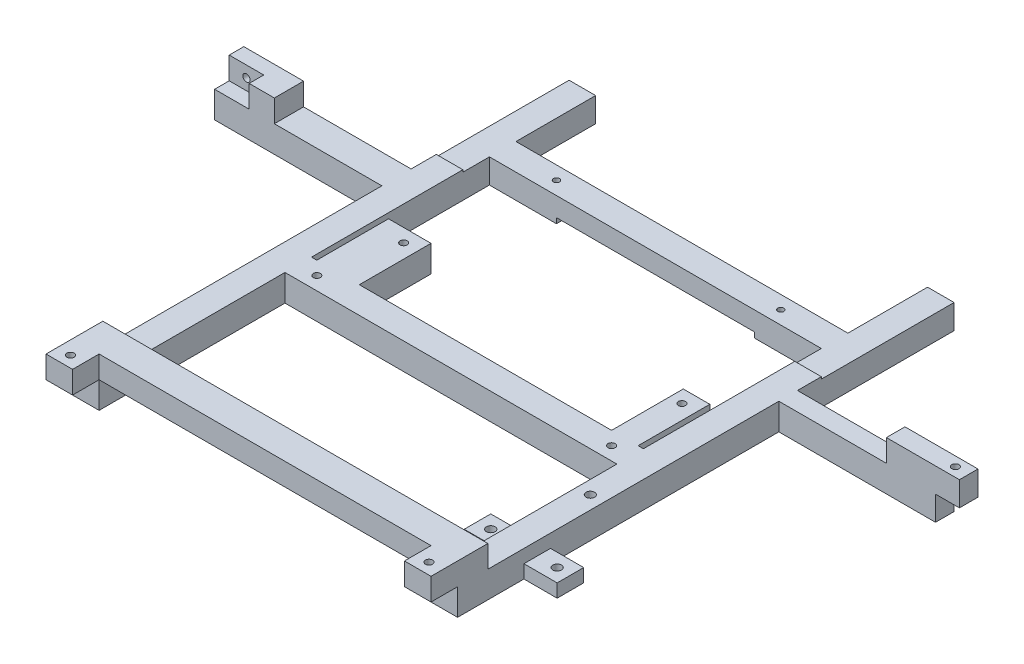
SolidWorks part; units mm, degrees
ref_plane "Front Plane" through (0, 0, 0) normal (0, 0, 1) x (1, 0, 0)
ref_plane "Top Plane" through (0, 0, 0) normal (0, 1, 0) x (1, 0, 0)
ref_plane "Right Plane" through (0, 0, 0) normal (1, 0, 0) x (0, 0, -1)
sketch "Sketch1" plane through (0, 0, 0) normal (0, 1, 0) x (1, 0, 0)
  line L0 (0, 125) -> (0, -125) construction
  line L1 (-125, 0) -> (125, 0) construction
  line L2 (-72.5, 93.5) -> (-72.5, -93.5)
  line L3 (-72.5, -93.5) -> (-62.5, -93.5)
  line L4 (-62.5, -93.5) -> (-62.5, -23.5)
  line L5 (-62.5, -23.5) -> (62.5, -23.5)
  line L6 (62.5, -23.5) -> (62.5, -93.5)
  line L7 (62.5, -93.5) -> (72.5, -93.5)
  line L8 (72.5, -93.5) -> (72.5, 93.5)
  line L9 (72.5, 93.5) -> (62.5, 93.5)
  line L10 (62.5, 93.5) -> (62.5, 63.5)
  line L11 (62.5, 63.5) -> (-62.5, 63.5)
  line L12 (-62.5, 63.5) -> (-62.5, 93.5)
  line L13 (-62.5, 93.5) -> (-72.5, 93.5)
  line L14 (-62.5, -13.5) -> (-60.5, -13.5)
  line L15 (62.5, -13.5) -> (62.5, 53.5)
  line L16 (62.5, 53.5) -> (-62.5, 53.5)
  line L17 (-62.5, 53.5) -> (-62.5, -13.5)
  line L18 (-62.5, -23.5) -> (-62.5, -13.5) construction
  line L19 (-62.5, 63.5) -> (-62.5, 53.5) construction
  line L20 (-60.5, -13.5) -> (-60.5, 13.5)
  line L21 (-60.5, 13.5) -> (-44.5, 13.5)
  line L22 (-44.5, 13.5) -> (-44.5, -13.5)
  line L23 (-44.5, -13.5) -> (50.5, -13.5)
  line L24 (50.5, -13.5) -> (50.5, 13.5)
  line L25 (50.5, 13.5) -> (60.5, 13.5)
  line L26 (60.5, 13.5) -> (60.5, -13.5)
  line L27 (60.5, -13.5) -> (62.5, -13.5)
  point P2 (0, 0)
  point P5 (0, 0)
  point P11 (-67.5, -93.5)
  point P32 (67.5, -93.5)
  dimension "D1" = 250
  dimension "D2" = 135
  dimension "D3" = 70
  dimension "D4" = 30
  dimension "D5" = 10
  dimension "D6" = 187
  dimension "D7" = 16
  dimension "D8" = 27
  dimension "D9" = 121
extrude "frame" add sketch "Sketch1" along normal blind 10
sketch "Sketch10" plane through (0, 10, 0) normal (0, 1, 0) x (1, 0, 0)
  line L0 (72.5, -93.5) -> (72.5, 93.5) construction
  line L1 (-72.5, 93.5) -> (72.5, 93.5)
  line L2 (-72.5, 93.5) -> (-72.5, 43.5)
  line L3 (-72.5, 43.5) -> (72.5, 43.5)
  line L4 (72.5, 93.5) -> (72.5, 43.5)
  dimension "D1" = 50
extrude "Cut-Extrude1" cut sketch "Sketch10" against normal blind 0.8
sketch "driver-screw-guides" plane through (0, 0, 0) normal (0, -1, 0) x (1, 0, 0)
  line L0 (0, 23.5) -> (0, -63.5) construction
  line L1 (-62.5, 23.5) -> (62.5, 23.5) construction
  line L2 (62.5, -63.5) -> (-62.5, -63.5) construction
  line L3 (55.5, 18.5) -> (55.5, -13.5) construction
  line L5 (50.5, -13.5) -> (60.5, -13.5) construction
  line L7 (-55.5, 18.5) -> (-55.5, -13.5) construction
  line L8 (-60.5, -13.5) -> (-44.5, -13.5) construction
  circle A0 centre (-55.5, 18.5) radius 2.5
  circle A1 centre (55.5, 18.5) radius 2.5
  circle A2 centre (-49.8, -8.5) radius 2.5
  circle A3 centre (55, -8.5) radius 2.5
  dimension "D5" = 5
  dimension "D1" = 111
  dimension "D2" = 5
  dimension "D3" = 1
  dimension "D4" = 5.7
  dimension "D6" = 32
hole_wizard "#6-32 Tapped Hole2" positions "Sketch12" profile "Sketch13" tap size "#6-32" standard "ANSI Inch" end condition through all
sketch "Sketch12" plane through (0, 0, 0) normal (0, -1, 0) x (-1, 0, 0)
  point P0 (55.5, -18.5)
  point P3 (49.8, 8.5)
  point P6 (-55, 8.5)
  point P9 (-55.5, -18.5)
sketch "Sketch13" plane through (-55.5, 0, 18.5) normal (1, 0, 0) x (0, 0, -1)
  line L0 (0, 0) -> (0, 10)
  line L1 (0, 10) -> (1.3525, 10)
  line L2 (1.3525, 10) -> (1.3525, 0)
  line L5 (1.3525, 0) -> (0, 0)
  line L11 (0, -6.35) -> (0, 107.95) construction
  dimension "Thru Tap Drill Dia." = 2.7051
  dimension "Thru Tap Drill Depth" = 10
cosmetic thread "Hole Thread3" parameters "D2"=3.5052
cosmetic thread "Hole Thread4" parameters "D2"=3.5052
cosmetic thread "Hole Thread5" parameters "D2"=3.5052
cosmetic thread "Hole Thread6" parameters "D2"=3.5052
sketch "controller-screw-guides" plane through (0, 0, 0) normal (0, -1, 0) x (1, 0, 0)
  line L0 (0, -63.5) -> (0, -53.5) construction
  line L1 (0, 23.5) -> (0, -63.5) construction
  line L2 (62.5, -63.5) -> (-62.5, -63.5) construction
  line L3 (62.5, -53.5) -> (-62.5, -53.5) construction
  circle A0 centre (-42.25, -58.5) radius 2.5
  circle A1 centre (42.25, -58.5) radius 2.5
  point P10 (0, -58.5)
  dimension "D2" = 5
  dimension "D1" = 84.5
hole_wizard "#4-40 Tapped Hole1" positions "Sketch15" profile "Sketch16" tap size "#4-40" standard "ANSI Inch" end condition through all
sketch "Sketch15" plane through (0, 0, 0) normal (0, -1, 0) x (-1, 0, 0)
  point P0 (42.25, 58.5)
  point P3 (-42.25, 58.5)
sketch "Sketch16" plane through (-42.25, 0, -58.5) normal (1, 0, 0) x (0, 0, -1)
  line L0 (0, 0) -> (0, 10)
  line L1 (0, 10) -> (1.1303, 10)
  line L2 (1.1303, 10) -> (1.1303, 0)
  line L5 (1.1303, 0) -> (0, 0)
  line L11 (0, -6.35) -> (0, 107.95) construction
  dimension "Thru Tap Drill Dia." = 2.2606
  dimension "Thru Tap Drill Depth" = 10
cosmetic thread "Hole Thread7" parameters "D2"=2.8448
cosmetic thread "Hole Thread8" parameters "D2"=2.8448
sketch "bottom-legs-s" plane through (0, 10, 0) normal (0, 1, 0) x (1, 0, 0)
  line L2 (-72.5, -103.5) -> (-72.5, -82.1)
  line L3 (-72.5, -82.1) -> (72.5, -82.1)
  line L4 (72.5, -82.1) -> (72.5, -103.5)
  line L5 (72.5, -93.5) -> (72.5, 43.5) construction
  line L7 (-62.5, -23.5) -> (62.5, -23.5) construction
  line L8 (-72.5, -103.5) -> (-62.5, -103.5)
  line L9 (-62.5, -103.5) -> (-62.5, -93.5)
  line L10 (-62.5, -93.5) -> (62.5, -93.5)
  line L11 (62.5, -93.5) -> (62.5, -103.5)
  line L12 (62.5, -103.5) -> (72.5, -103.5)
  line L13 (-72.5, -93.5) -> (-62.5, -93.5) construction
  line L14 (-72.5, 43.5) -> (-72.5, -93.5) construction
  dimension "D1" = 10
  dimension "D3" = 58.6
extrude "bottom-legs" add sketch "bottom-legs-s" along normal blind 8.4
sketch "side-arms-s" plane through (0, 10, 0) normal (0, 1, 0) x (1, 0, 0)
  line L0 (-72.5, 43.5) -> (-72.5, -82.1) construction
  line L1 (-72.5, 34) -> (-135.5, 34)
  line L2 (-72.5, 34) -> (-72.5, 23)
  line L3 (-72.5, 23) -> (-135.5, 23)
  line L4 (-135.5, 34) -> (-135.5, 23)
  line L5 (72.5, -82.1) -> (72.5, 43.5) construction
  line L6 (72.5, 34.5) -> (131.5, 34.5)
  line L7 (72.5, 34.5) -> (72.5, 27.5)
  line L8 (72.5, 27.5) -> (131.5, 27.5)
  line L9 (131.5, 34.5) -> (131.5, 27.5)
  line L10 (-72.5, -103.5) -> (-62.5, -103.5) construction
  line L11 (62.5, -103.5) -> (72.5, -103.5) construction
  point P14 (-72.5, 28.5)
  point P17 (72.5, 31)
  dimension "D1" = 11
  dimension "D2" = 132
  dimension "D3" = 63
  dimension "D4" = 134.5
  dimension "D5" = 7
  dimension "D6" = 59
extrude "side-arms" add sketch "side-arms-s" against normal up to surface (10 mm away) up to face at (-42.25, 0, -59.6303)
sketch "side-tabs-s" plane through (0, 10, 0) normal (0, 1, 0) x (1, 0, 0)
  line L0 (-135.5, 34) -> (-135.5, 23) construction
  line L1 (-135.5, 34) -> (-122.5, 34)
  line L2 (-135.5, 34) -> (-135.5, 28.5)
  line L3 (-135.5, 28.5) -> (-122.5, 28.5)
  line L4 (-122.5, 34) -> (-122.5, 28.5)
  line L5 (72.5, 27.5) -> (131.5, 27.5) construction
  line L6 (122.5, 27.5) -> (131.5, 27.5)
  line L7 (122.5, 27.5) -> (122.5, 34.5)
  line L8 (122.5, 34.5) -> (131.5, 34.5)
  line L9 (131.5, 27.5) -> (131.5, 34.5)
  line L12 (131.5, 34.5) -> (72.5, 34.5) construction
  point P9 (-135.5, 28.5)
  dimension "D1" = 13
  dimension "D2" = 9
extrude "side-tabs" add sketch "side-tabs-s" along normal blind 8.4
sketch "left-screws-s" plane through (0, 0, -28.5) normal (0, 0, 1) x (1, 0, 0)
  line L0 (-135.5, 18.4) -> (-122.5, 18.4) construction
  line L1 (-122.5, 18.4) -> (-122.5, 10) construction
  circle A0 centre (-129, 14.2) radius 3.5
  point P5 (-129, 18.4)
  point P9 (-122.5, 14.2)
  dimension "D1" = 7
sketch "bottom-screws-s" plane through (0, 18.4, 0) normal (0, 1, 0) x (1, 0, 0)
  line L0 (62.5, -103.5) -> (72.5, -103.5) construction
  line L1 (-72.5, -103.5) -> (-62.5, -103.5) construction
  circle A0 centre (67.5, -99.27) radius 3.5
  circle A1 centre (-67.5, -99.27) radius 3.5
  point P6 (67.5, -103.5)
  point P11 (-67.5, -103.5)
  dimension "D2" = 7
  dimension "D3" = 7
  dimension "D1" = 4.23
hole_wizard "bottom-screws" positions "Sketch25" profile "Sketch26" tap size "#6-32" standard "ANSI Inch" end condition through all
sketch "Sketch25" plane through (0, 18.4, 0) normal (0, 1, 0) x (1, 0, 0)
  point P0 (-67.5, -99.27)
  point P3 (67.5, -99.27)
sketch "Sketch26" plane through (-67.5, 18.4, 99.27) normal (1, 0, 0) x (0, 0, 1)
  line L0 (0, 0) -> (0, 18.4)
  line L1 (0, 18.4) -> (1.3525, 18.4)
  line L2 (1.3525, 18.4) -> (1.3525, 0)
  line L5 (1.3525, 0) -> (0, 0)
  line L11 (0, -6.35) -> (0, 107.95) construction
  dimension "Thru Tap Drill Dia." = 2.7051
  dimension "Thru Tap Drill Depth" = 18.4
cosmetic thread "Hole Thread13" parameters "D2"=3.5052
cosmetic thread "Hole Thread14" parameters "D2"=3.5052
hole_wizard "left-screw" positions "Sketch27" profile "Sketch28" tap size "#6-32" standard "ANSI Inch" end condition through all
sketch "Sketch27" plane through (0, 0, -28.5) normal (0, 0, 1) x (1, 0, 0)
  point P0 (-129, 14.2)
sketch "Sketch28" plane through (-129, 14.2, -28.5) normal (1, 0, 0) x (0, -1, 0)
  line L0 (0, 0) -> (0, 65)
  line L1 (0, 65) -> (1.3525, 65)
  line L2 (1.3525, 65) -> (1.3525, 0)
  line L5 (1.3525, 0) -> (0, 0)
  line L11 (0, -6.35) -> (0, 107.95) construction
  dimension "Thru Tap Drill Dia." = 2.7051
  dimension "Thru Tap Drill Depth" = 65
cosmetic thread "Hole Thread15" parameters "D2"=3.5052
sketch "right-foot-s" plane through (131.5, 0, 0) normal (1, 0, 0) x (0, 0, -1)
  line L0 (34.5, 0) -> (34.5, 18.4) construction
  line L1 (27.5, 18.4) -> (34.5, 18.4)
  line L2 (27.5, 18.4) -> (27.5, 9.2)
  line L3 (27.5, 9.2) -> (34.5, 9.2)
  line L4 (34.5, 18.4) -> (34.5, 9.2)
extrude "right-foot" add sketch "right-foot-s" along normal blind 9
sketch "right-screw-s" plane through (0, 9.2, 0) normal (0, -1, 0) x (1, 0, 0)
  line L0 (140.5, -27.5) -> (140.5, -34.5) construction
  circle A0 centre (135.5, -31) radius 2.5
  point P5 (140.5, -31)
  dimension "D2" = 5
  dimension "D1" = 5
hole_wizard "right-screw" positions "Sketch31" profile "Sketch32" tap size "#6-32" standard "ANSI Inch" end condition through all
sketch "Sketch31" plane through (0, 9.2, 0) normal (0, -1, 0) x (-1, 0, 0)
  point P0 (-135.5, 31)
sketch "Sketch32" plane through (135.5, 9.2, -31) normal (1, 0, 0) x (0, 0, -1)
  line L0 (0, 0) -> (0, 9.2)
  line L1 (0, 9.2) -> (1.3525, 9.2)
  line L2 (1.3525, 9.2) -> (1.3525, 0)
  line L5 (1.3525, 0) -> (0, 0)
  line L11 (0, -6.35) -> (0, 107.95) construction
  dimension "Thru Tap Drill Dia." = 2.7051
  dimension "Thru Tap Drill Depth" = 9.2
cosmetic thread "Hole Thread16" parameters "D2"=3.5052
sketch "control-board-relief-s" plane through (0, 0, 0) normal (0, -1, 0) x (1, 0, 0)
  line L0 (62.5, -63.5) -> (-62.5, -63.5) construction
  line L1 (37.25, -63.5) -> (-37.25, -63.5)
  line L2 (37.25, -63.5) -> (37.25, -53.5)
  line L3 (37.25, -53.5) -> (-37.25, -53.5)
  line L4 (-37.25, -63.5) -> (-37.25, -53.5)
  line L5 (62.5, -53.5) -> (-62.5, -53.5) construction
  line L7 (0, -53.5) -> (0, -63.5) construction
  point P8 (0, -63.5)
  dimension "D1" = 5
extrude "control-board-relief" cut sketch "control-board-relief-s" against normal blind 2
sketch "monitor-side-guides-s" plane through (0, 10, 0) normal (0, 1, 0) x (1, 0, 0)
  line L0 (-72.5, 34) -> (-122.5, 34) construction
  line L1 (-122.5, 34) -> (-113, 34)
  line L2 (-122.5, 34) -> (-122.5, 23)
  line L3 (-122.5, 23) -> (-113, 23)
  line L4 (-113, 34) -> (-113, 23)
  line L5 (-135.5, 23) -> (-72.5, 23) construction
  line L6 (122.5, 34.5) -> (72.5, 34.5) construction
  line L7 (113, 34.5) -> (122.5, 34.5)
  line L8 (113, 34.5) -> (113, 27.5)
  line L9 (113, 27.5) -> (122.5, 27.5)
  line L10 (122.5, 34.5) -> (122.5, 27.5)
  line L11 (72.5, 27.5) -> (122.5, 27.5) construction
  line L12 (0, 0) -> (0, 63.5) construction
  line L13 (62.5, 63.5) -> (-62.5, 63.5) construction
  line L14 (-113, 23) -> (0, 23) construction
  line L15 (113, 27.5) -> (0, 27.5) construction
  dimension "D1" = 226
extrude "side-monitor-guides" add sketch "monitor-side-guides-s" along normal up to surface (8.4 mm away) up to face at (-129, 18.4, -31.25)
sketch "led-board-s" plane through (0, 0, 0) normal (0, -1, 0) x (1, 0, 0)
  line L0 (85, 63.5) -> (72.5, 63.5) construction
  line L1 (85, 58.5) -> (50, 58.5)
  line L2 (85, 58.5) -> (85, 68.5)
  line L3 (85, 68.5) -> (50, 68.5)
  line L4 (50, 58.5) -> (50, 68.5)
  line L5 (72.5, 93.5) -> (72.5, -27.5) construction
  line L6 (50, 63.5) -> (62.5, 63.5) construction
  line L7 (62.5, 23.5) -> (62.5, 93.5) construction
  line L9 (-62.5, 23.5) -> (62.5, 23.5) construction
  dimension "D1" = 10
  dimension "D2" = 35
  dimension "D3" = 40
extrude "led-board" add sketch "led-board-s" against normal blind 5
sketch "led-screws-s" plane through (0, 0, 0) normal (0, -1, 0) x (1, 0, 0)
  line L0 (85, 58.5) -> (85, 68.5) construction
  line L1 (67.5, 93.5) -> (67.5, -93.5) construction
  line L2 (62.5, 93.5) -> (72.5, 93.5) construction
  line L3 (72.5, -93.5) -> (62.5, -93.5) construction
  line L4 (80, 63.5) -> (55, 63.5) construction
  circle A0 centre (80, 63.5) radius 5
  circle A1 centre (55, 63.5) radius 5
  circle A2 centre (67.5, 38.5) radius 5
  point P7 (85, 63.5)
  point P14 (67.5, -93.5)
  dimension "D1" = 10
  dimension "D2" = 25
  dimension "D3" = 25
hole_wizard "#4 Clearance Hole1" positions "3DSketch1" profile "Sketch35" hole size "#4" standard "ANSI Inch" end condition up to next
sketch3d "3DSketch1"
  point P0 (67.5, 0, 38.5)
  point P3 (80, 0, 63.5)
  point P6 (55, 0, 63.5)
sketch "Sketch35" plane through (67.5, 0, 38.5) normal (1, 0, 0) x (0, 0, -1)
  line L0 (0, 0) -> (0, 10)
  line L1 (0, 10) -> (1.6319, 10)
  line L2 (1.6319, 10) -> (1.6319, 0)
  line L5 (1.6319, 0) -> (0, 0)
  line L11 (0, -6.35) -> (0, 107.95) construction
  dimension "Thru Hole Dia." = 3.2639
  dimension "Thru Hole Depth" = 10
